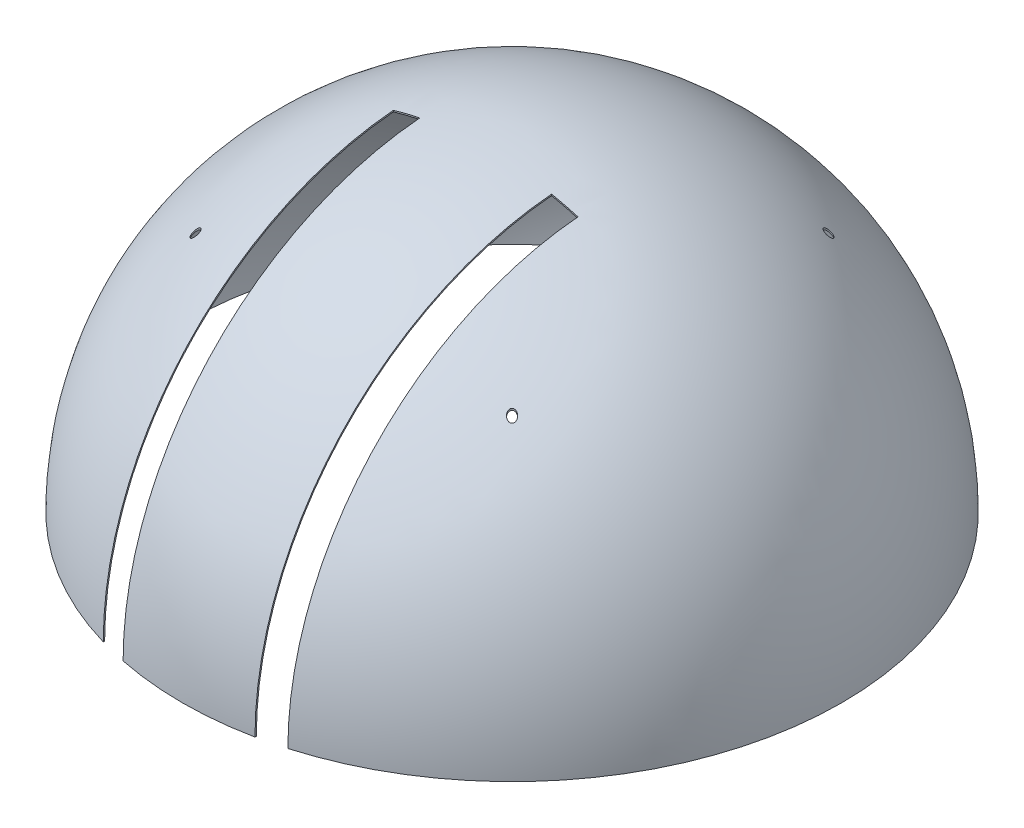
SolidWorks part; units mm, degrees
material "1060 Сплав"
ref_plane "Спереди XY" through (0, 0, 0) normal (0, 0, 1) x (1, 0, 0)
ref_plane "Сверху XZ" through (0, 0, 0) normal (0, 1, 0) x (1, 0, 0)
ref_plane "Справа ZY" through (0, 0, 0) normal (1, 0, 0) x (0, 0, -1)
sketch "Эскиз1" plane through (0, 0, 0) normal (0, 1, 0) x (1, 0, 0)
  line L0 (-250, 0) -> (250, 0)
  arc A0 (250, 0) -> (-250, 0) centre (0, 0) ccw
  dimension "D1" = 250
revolve "Повернуть1" add sketch "Эскиз1" angle 180 about L0
shell "Оболочка1" thickness 1
sketch "Эскиз2" plane through (0, 0, 0) normal (0, 1, 0) x (1, 0, 0)
  line L0 (0, 334.5014) -> (0, -414.6086) construction
  line L1 (0, -250) -> (303.1081, -250) construction
  line L2 (-70, -250) -> (-50, -250)
  line L3 (70, -250) -> (50, -250)
  line L4 (70, -250) -> (70, -20)
  line L5 (70, -20) -> (50, -20)
  line L6 (50, -250) -> (50, -20)
  line L7 (-70, -250) -> (-70, -20)
  line L8 (-70, -20) -> (-50, -20)
  line L9 (-50, -250) -> (-50, -20)
  circle A0 centre (0, 0) radius 250 construction
  dimension "D1" = 20
  dimension "D2" = 20
  dimension "D3" = 50
extrude "Вырез-Вытянуть1" cut sketch "Эскиз2" along normal through all both and the other way through all
sketch "Эскиз3" plane through (0, 0, 0) normal (0, 1, 0) x (1, 0, 0)
  line L0 (50, -20) -> (70, -20) construction
  line L1 (70, -20) -> (70, -240) construction
  circle A0 centre (120, -120) radius 3
  circle A1 centre (-120, -120) radius 3
  circle A2 centre (-120, 120) radius 3
  circle A3 centre (120, 120) radius 3
  point P4 (60, -20)
  point P15 (0, 0)
  dimension "D3" = 6
  dimension "D1" = 100
  dimension "D2" = 50
  dimension "D4" = 4
extrude "Вырез-Вытянуть2" cut sketch "Эскиз3" along normal through all both and the other way through all
